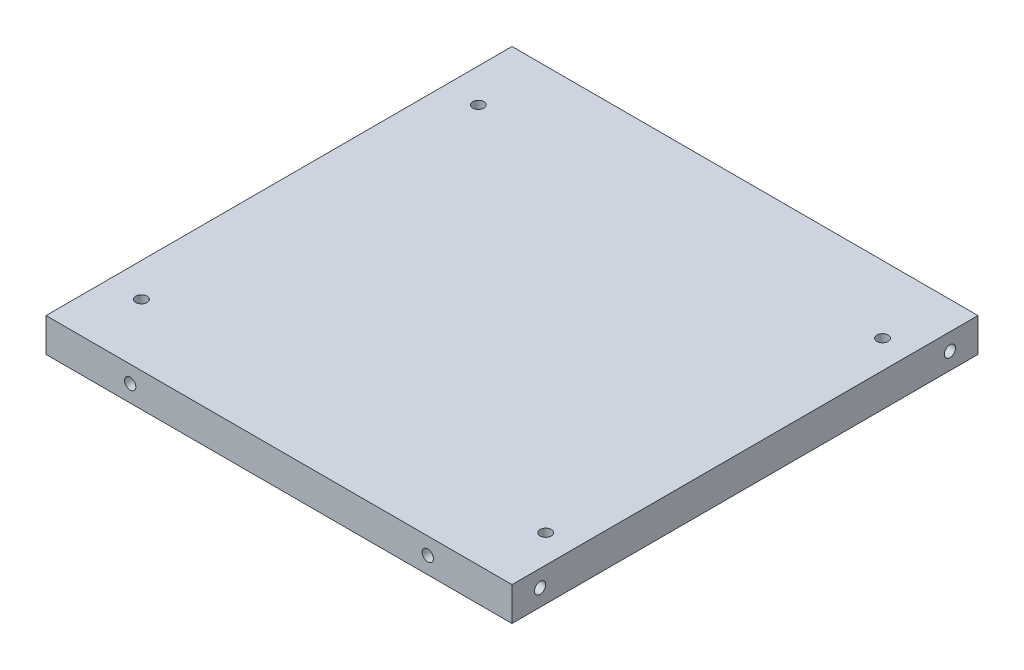
SolidWorks part; units mm, degrees
material "AISI 1020"
ref_plane "Front Plane" through (0, 0, 0) normal (0, 0, 1) x (1, 0, 0)
ref_plane "Top Plane" through (0, 0, 0) normal (0, 1, 0) x (1, 0, 0)
ref_plane "Right Plane" through (0, 0, 0) normal (1, 0, 0) x (0, 0, -1)
sketch "Sketch1" plane through (0, 0, 0) normal (0, 1, 0) x (1, 0, 0)
  line L1 (0, 0) -> (83, 0)
  line L2 (0, 0) -> (0, 83)
  line L3 (0, 83) -> (83, 83)
  line L4 (83, 0) -> (83, 83)
  dimension "D1" = 83
  dimension "D2" = 83
extrude "Boss-Extrude1" add sketch "Sketch1" along normal blind 6
sketch "Sketch2" plane through (0, 6, 0) normal (0, 1, 0) x (1, 0, 0)
  line L0 (83, 83) -> (0, 83) construction
  line L1 (0, 83) -> (0, 0) construction
  circle A0 centre (6, 71) radius 1
  dimension "D1" = 2
  dimension "D3" = 6
  dimension "D2" = 12
extrude "Cut-Extrude1" cut sketch "Sketch2" against normal blind 6
pattern_linear "LPattern1" count 2 spacing 72 along (1, 0, 0) count 2 spacing 60 along (0, 0, 1) of "Cut-Extrude1"
sketch "Sketch3" plane through (0, 0, 0) normal (-1, 0, 0) x (0, 0, 1)
  line L0 (-83, 3) -> (-5, 3) construction
  line L1 (-83, 6) -> (-83, 0) construction
  line L2 (0, 6) -> (0, 0) construction
  circle A0 centre (-78, 3) radius 1
  circle A1 centre (-5, 3) radius 1
  dimension "D1" = 5
  dimension "D3" = 2
  dimension "D4" = 2
  dimension "D2" = 5
extrude "Cut-Extrude2" cut sketch "Sketch3" against normal blind 10
ref_plane "Plane1" through (41.5, 0, 0) normal (-1, 0, 0) x (0, 0, 1)
mirror "Mirror1" about plane through (41.5, 0, 0) normal (-1, 0, 0) of "Cut-Extrude2"
sketch "Sketch4" plane through (0, 0, 0) normal (0, 0, 1) x (1, 0, 0)
  line L0 (0, 3) -> (83, 3) construction
  line L1 (0, 6) -> (0, 0) construction
  line L2 (83, 6) -> (83, 0) construction
  circle A0 centre (15, 3) radius 1
  circle A1 centre (68, 3) radius 1
  point P10 (33.5738, 3)
  point P11 (13.4492, 3)
  dimension "D1" = 2
  dimension "D2" = 2
  dimension "D3" = 15
  dimension "D4" = 15
extrude "Cut-Extrude3" cut sketch "Sketch4" against normal blind 10
ref_plane "Plane2" through (0, 0, -41.5) normal (0, 0, 1) x (1, 0, 0)
mirror "Mirror2" about plane through (0, 0, -41.5) normal (0, 0, 1) of "Cut-Extrude3"
